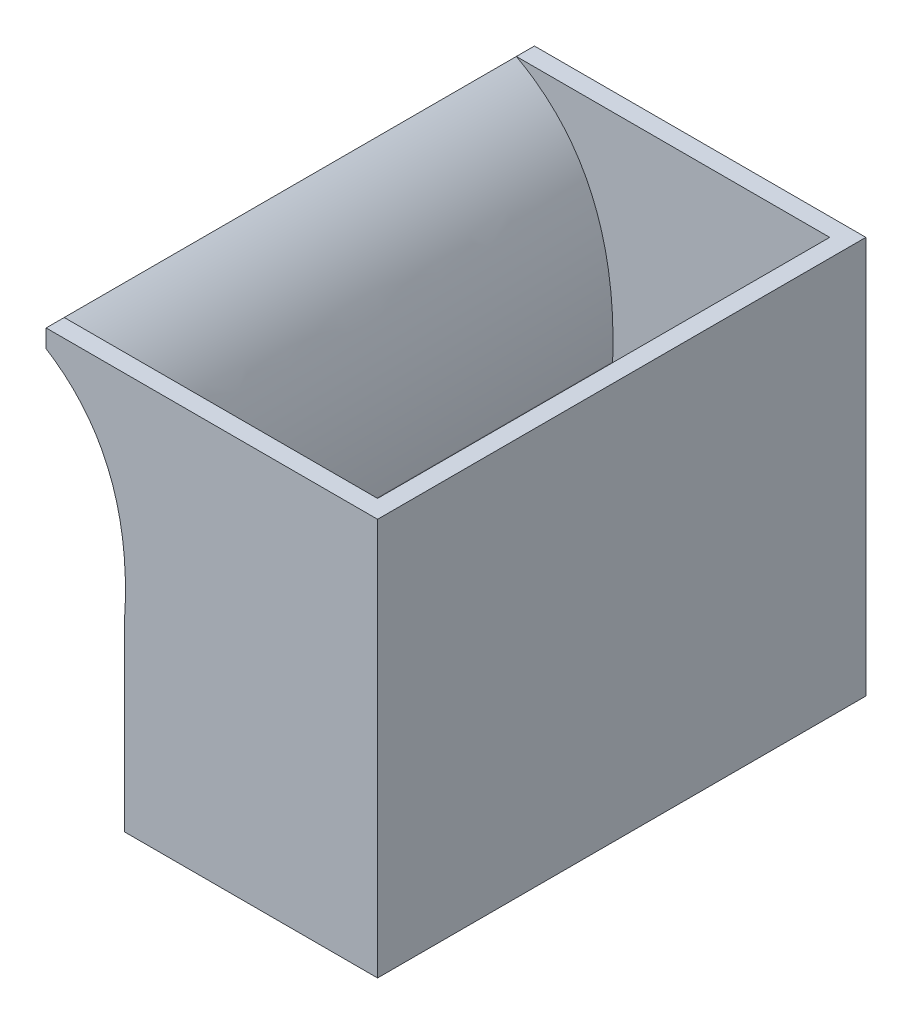
SolidWorks part; units mm, degrees
ref_plane "Front Plane" through (0, 0, 0) normal (0, 0, 1) x (1, 0, 0)
ref_plane "Top Plane" through (0, 0, 0) normal (0, 1, 0) x (1, 0, 0)
ref_plane "Right Plane" through (0, 0, 0) normal (1, 0, 0) x (0, 0, -1)
sketch "Sketch7" plane through (0, 0, 0) normal (0, 0, 1) x (1, 0, 0)
  line L0 (0, 0) -> (0, 254)
  line L1 (-32.9024, 278.5282) -> (-32.9024, 303.9282)
  line L2 (76.981, 0) -> (102.381, 0)
  line L3 (102.381, 0) -> (407.181, 0)
  line L13 (407.181, 0) -> (432.581, 0)
  line L14 (407.181, 0) -> (407.181, 303.9282)
  line L15 (407.181, 303.9282) -> (432.581, 303.9282)
  line L16 (432.581, 0) -> (432.581, 303.9282)
  spline S0 degree 2 poles (76.981, 0) (100.4422, 194.3224) (-32.9024, 278.5282) knots 0 0 0 1 1 1
  spline S1 degree 2 poles (102.381, 0) (111.9982, 241.3295) (-53.2276, 313.8434) knots 0 0 0 1 1 1
extrude "Boss-Extrude2" add sketch "Sketch7" along normal blind 635 contours L13 L16 L15 L14 | L2 S1 L1 S0
sketch "Sketch9" plane through (0, 0, 635) normal (0, 0, 1) x (1, 0, 0)
  line L1 (432.581, 0) -> (-32.9024, 0)
  line L2 (432.581, 0) -> (432.581, 303.9282)
  line L3 (432.581, 303.9282) -> (-32.9024, 303.9282)
  line L4 (-32.9024, 0) -> (-32.9024, 303.9282)
extrude "Boss-Extrude3" add sketch "Sketch9" along normal blind 25.4
sketch "Sketch10" plane through (0, 0, 0) normal (0, 0, -1) x (-1, 0, 0)
  line L1 (-432.581, 303.9282) -> (32.9024, 303.9282)
  line L2 (-432.581, 303.9282) -> (-432.581, 0)
  line L3 (-432.581, 0) -> (32.9024, 0)
  line L4 (32.9024, 303.9282) -> (32.9024, 0)
extrude "Boss-Extrude4" add sketch "Sketch10" along normal blind 25.4
sketch "Sketch11" plane through (0, 0, 635) normal (0, 0, -1) x (-1, 0, 0)
  line L0 (32.9024, 278.5282) -> (32.9024, 0)
  line L1 (32.9024, 0) -> (-76.981, 0)
  spline S0 degree 2 poles (-76.981, 0) (-93.0815, 219.1077) (57.2059, 291.9394) knots 0 0 0 1 1 1
  line M1 (32.9024, 0) -> (32.9024, 278.5282)
  spline M2 degree 2 poles (32.9024, 278.5282) (-100.4422, 194.3224) (-76.981, 0) knots 0 0 0 1 1 1
  line M3 (-76.981, 0) -> (32.9024, 0)
extrude "Cut-Extrude1" cut sketch "Sketch11" against normal blind 125.476 and the other way blind 2380.234 contours S0 M3 M1 M2
sketch "Sketch12" plane through (0, 0, 0) normal (0, -1, 0) x (1, 0, 0)
  line L1 (76.981, 660.4) -> (432.581, 660.4)
  line L2 (76.981, 660.4) -> (76.981, -25.4)
  line L3 (76.981, -25.4) -> (432.581, -25.4)
  line L4 (432.581, 660.4) -> (432.581, -25.4)
extrude "Boss-Extrude5" add sketch "Sketch12" along normal blind 254
sketch "Sketch13" plane through (0, 0, 0) normal (0, 1, 0) x (1, 0, 0)
  line L1 (102.381, -635) -> (407.181, -635)
  line L2 (102.381, -635) -> (102.381, 0)
  line L3 (102.381, 0) -> (407.181, 0)
  line L4 (407.181, -635) -> (407.181, 0)
extrude "Cut-Extrude2" cut sketch "Sketch13" against normal blind 551.942
